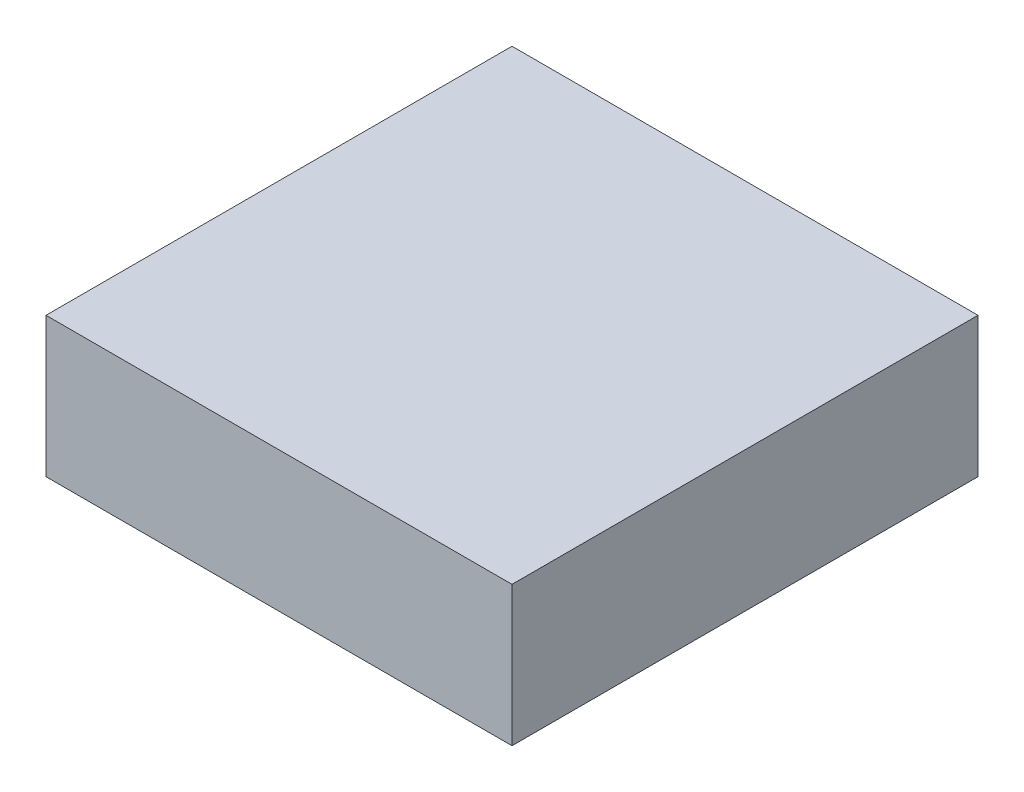
SolidWorks part; units mm, degrees
ref_plane "前视基准面" through (0, 0, 0) normal (0, 0, 1) x (1, 0, 0)
ref_plane "上视基准面" through (0, 0, 0) normal (0, 1, 0) x (1, 0, 0)
ref_plane "右视基准面" through (0, 0, 0) normal (1, 0, 0) x (0, 0, -1)
other "Configuration Table"
sketch "草图1" plane through (-4.8007, 0, -9.6031) normal (0, 1, 0) x (1, 0, 0)
  line L1 (-179.9466, 83.082) -> (-159.9466, 83.082)
  line L2 (-179.9466, 83.082) -> (-179.9466, 63.082)
  line L3 (-179.9466, 63.082) -> (-159.9466, 63.082)
  line L4 (-159.9466, 83.082) -> (-159.9466, 63.082)
  dimension "D1" = 20
  dimension "D2" = 20
extrude "凸台-拉伸1" add sketch "草图1" along normal blind 6
